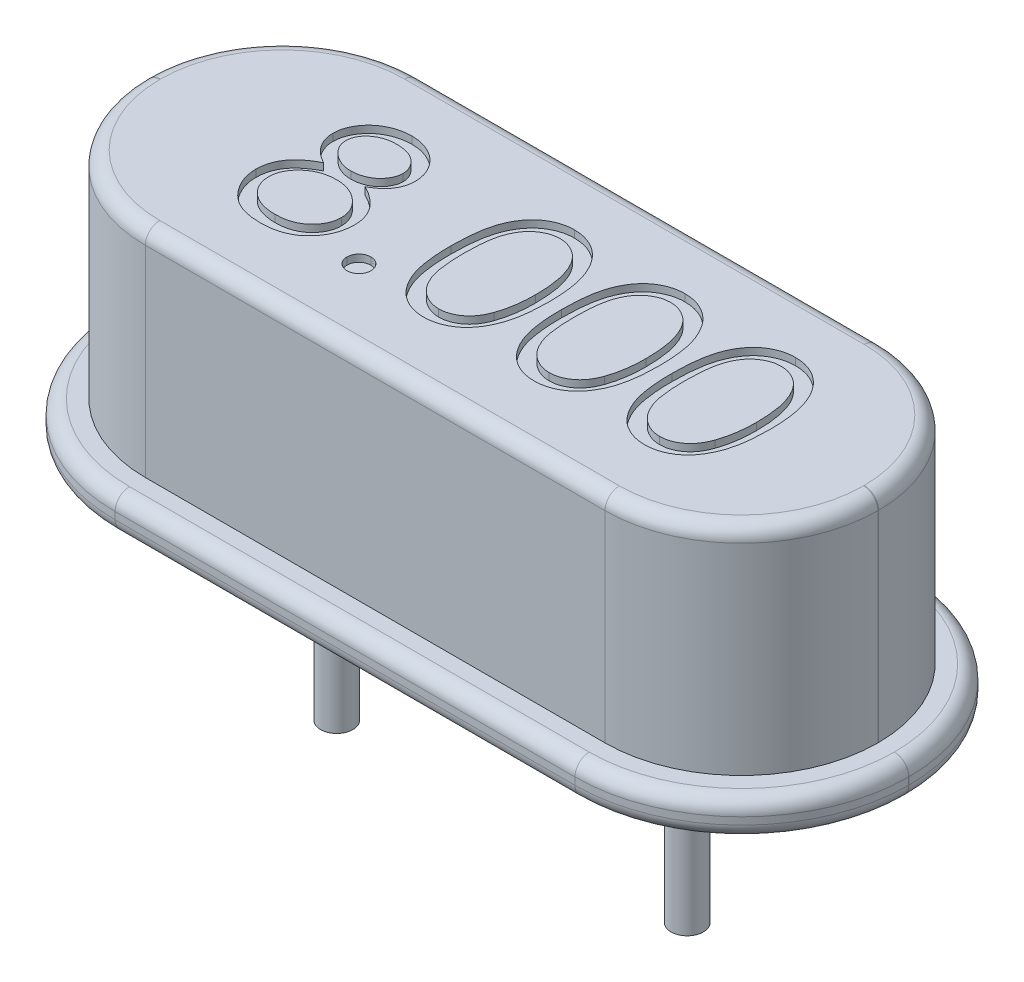
SolidWorks part; units mm, degrees
ref_plane "Front Plane" through (0, 0, 0) normal (0, 0, 1) x (1, 0, 0)
ref_plane "Top Plane" through (0, 0, 0) normal (0, 1, 0) x (1, 0, 0)
ref_plane "Right Plane" through (0, 0, 0) normal (1, 0, 0) x (0, 0, -1)
sketch "Sketch1" plane through (0, 0, 0) normal (0, 1, 0) x (1, 0, 0)
  line L1 (-3.201, -2.325) -> (3.201, -2.325)
  line L2 (-5.525, -0.001) -> (-5.525, 0.001)
  line L3 (-3.201, 2.325) -> (3.201, 2.325)
  line L4 (5.525, -0.001) -> (5.525, 0.001)
  line L5 (-5.525, -2.325) -> (5.525, 2.325) construction
  line L6 (-5.525, 2.325) -> (5.525, -2.325) construction
  arc A0 (3.201, 2.325) -> (5.525, 0.001) centre (3.201, 0.001) cw
  arc A1 (3.201, -2.325) -> (5.525, -0.001) centre (3.201, -0.001) ccw
  arc A2 (-3.201, -2.325) -> (-5.525, -0.001) centre (-3.201, -0.001) cw
  arc A3 (-5.525, 0.001) -> (-3.201, 2.325) centre (-3.201, 0.001) cw
  point P0 (0, 0)
  dimension "D3" = 2.324
  dimension "D1" = 4.65
  dimension "D2" = 11.05
extrude "Boss-Extrude1" add sketch "Sketch1" along normal blind 0.5
sketch "Sketch2" plane through (0, 0.5, 0) normal (0, 1, 0) x (1, 0, 0)
  line L1 (-3.2, -1.905) -> (3.2, -1.905)
  line L2 (-5.1, -0.005) -> (-5.1, 0.005)
  line L3 (-3.2, 1.905) -> (3.2, 1.905)
  line L4 (5.1, -0.005) -> (5.1, 0.005)
  line L5 (-5.1, -1.905) -> (5.1, 1.905) construction
  line L6 (-5.1, 1.905) -> (5.1, -1.905) construction
  arc A0 (3.2, 1.905) -> (5.1, 0.005) centre (3.2, 0.005) cw
  arc A1 (3.2, -1.905) -> (5.1, -0.005) centre (3.2, -0.005) ccw
  arc A2 (-3.2, -1.905) -> (-5.1, -0.005) centre (-3.2, -0.005) cw
  arc A3 (-5.1, 0.005) -> (-3.2, 1.905) centre (-3.2, 0.005) cw
  point P0 (0, 0)
  dimension "D3" = 1.9
  dimension "D1" = 3.81
  dimension "D2" = 10.2
extrude "Boss-Extrude2" add sketch "Sketch2" along normal blind 3
fillet "Fillet1" radius 0.2 24 edges at (-4.8443, 0, 1.6443) (-5.525, 0, 0) (-4.8443, 0, -1.6443) (0, 0, -2.325) (4.8443, 0, -1.6443) (5.525, 0, 0) (4.8443, 0, 1.6443) (-4.8443, 0.5, 1.6443) (-5.525, 0.5, 0) (-4.8443, 0.5, -1.6443) (0, 0.5, -2.325) (4.8443, 0.5, -1.6443) (5.525, 0.5, 0) (4.8443, 0.5, 1.6443) (-4.5435, 3.5, 1.3485) (-5.1, 3.5, 0) (-4.5435, 3.5, -1.3485) (0, 3.5, -1.905) (4.5435, 3.5, -1.3485) (5.1, 3.5, 0) (4.5435, 3.5, 1.3485) (0, 0, 2.325) (0, 0.5, 2.325) (0, 3.5, 1.905)
sketch "Sketch3" plane through (0, 0, 0) normal (0, -1, 0) x (1, 0, 0)
  circle A0 centre (-2.44, 0) radius 0.225
  circle A1 centre (2.44, 0) radius 0.225
  dimension "D2" = 0.45
  dimension "D4" = 0.45
  dimension "D1" = 2.44
  dimension "D3" = 2.44
extrude "Boss-Extrude3" add sketch "Sketch3" along normal blind 3
sketch "Sketch4" plane through (0, 3.5, 0) normal (0, 1, 0) x (1, 0, 0)
  text T0 "8.000" font "Century Gothic" height 2
extrude "Cut-Extrude1" cut sketch "Sketch4" against normal blind 0.1
